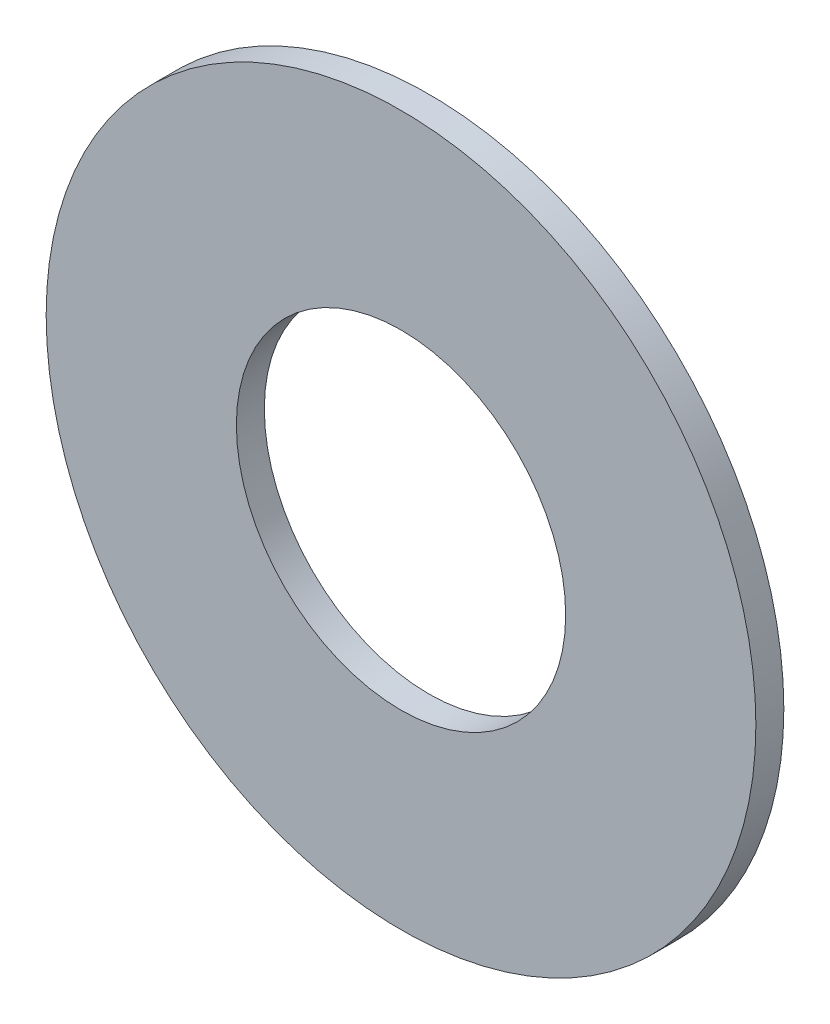
SolidWorks part; units mm, degrees
ref_plane "Front Plane" through (0, 0, 0) normal (0, 0, 1) x (1, 0, 0)
ref_plane "Top Plane" through (0, 0, 0) normal (0, 1, 0) x (1, 0, 0)
ref_plane "Right Plane" through (0, 0, 0) normal (1, 0, 0) x (0, 0, -1)
sketch "Sketch1" plane through (0, 0, 0) normal (0, 0, 1) x (1, 0, 0)
  line L0 (-4.7625, 0) -> (4.7625, 0) construction
  circle A0 centre (0, 0) radius 10.3188 construction
  circle A1 centre (0, 0) radius 4.7879 construction
  dimension "OD" = 20.6375
  dimension "ID" = 9.5758
  dimension "For Shaft Diameter" = 9.525
sketch "Sketch2" plane through (0, 0, 0) normal (1, 0, 0) x (0, 0, -1)
  line L4 (0.4064, 10.3188) -> (-0.4064, 10.3188) construction
  point P0 (0, 10.3188)
  dimension "Thickness" = 0.8128
sketch "Sketch3" plane through (0, 0, 0) normal (0, 0, 1) x (1, 0, 0)
  circle A0 centre (0, 0) radius 4.7879 construction
  circle A1 centre (0, 0) radius 10.3188 construction
  circle A3 centre (0, 0) radius 4.7879
  circle A5 centre (0, 0) radius 10.3188
extrude "Boss-Extrude1" add sketch "Sketch3" against normal up to vertex (0.4064 mm away) and the other way up to vertex (0.4064 mm away)
equation "\"D1\"= \"Thickness@Sketch2\""
